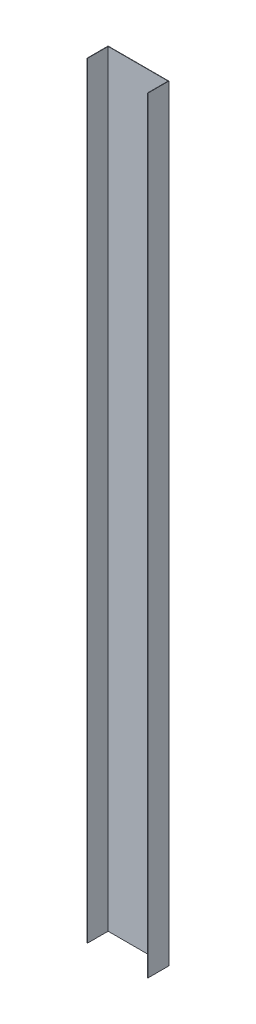
SolidWorks part; units mm, degrees
ref_plane "Front Plane" through (0, 0, 0) normal (0, 0, 1) x (1, 0, 0)
ref_plane "Top Plane" through (0, 0, 0) normal (0, 1, 0) x (1, 0, 0)
ref_plane "Right Plane" through (0, 0, 0) normal (1, 0, 0) x (0, 0, -1)
sketch "Sketch1" plane through (0, 0, 0) normal (0, 1, 0) x (1, 0, 0)
  line L0 (0, 0) -> (0, 31.219)
  line L1 (0, 31.219) -> (91.013, 31.219)
  line L2 (91.013, 31.219) -> (91.013, 0)
  line L3 (91.013, 0) -> (91.544, 0)
  line L4 (91.544, 0) -> (91.544, 31.75)
  line L5 (91.544, 31.75) -> (-0.531, 31.75)
  line L6 (-0.531, 31.75) -> (-0.531, 0)
  line L7 (-0.531, 0) -> (0, 0)
  line L8 (45.5065, 31.75) -> (45.5065, 31.219) construction
  dimension "D1" = 0.531
  dimension "D2" = 92.075
  dimension "D3" = 31.75
extrude "Boss-Extrude1" add sketch "Sketch1" along normal blind 1162.05
